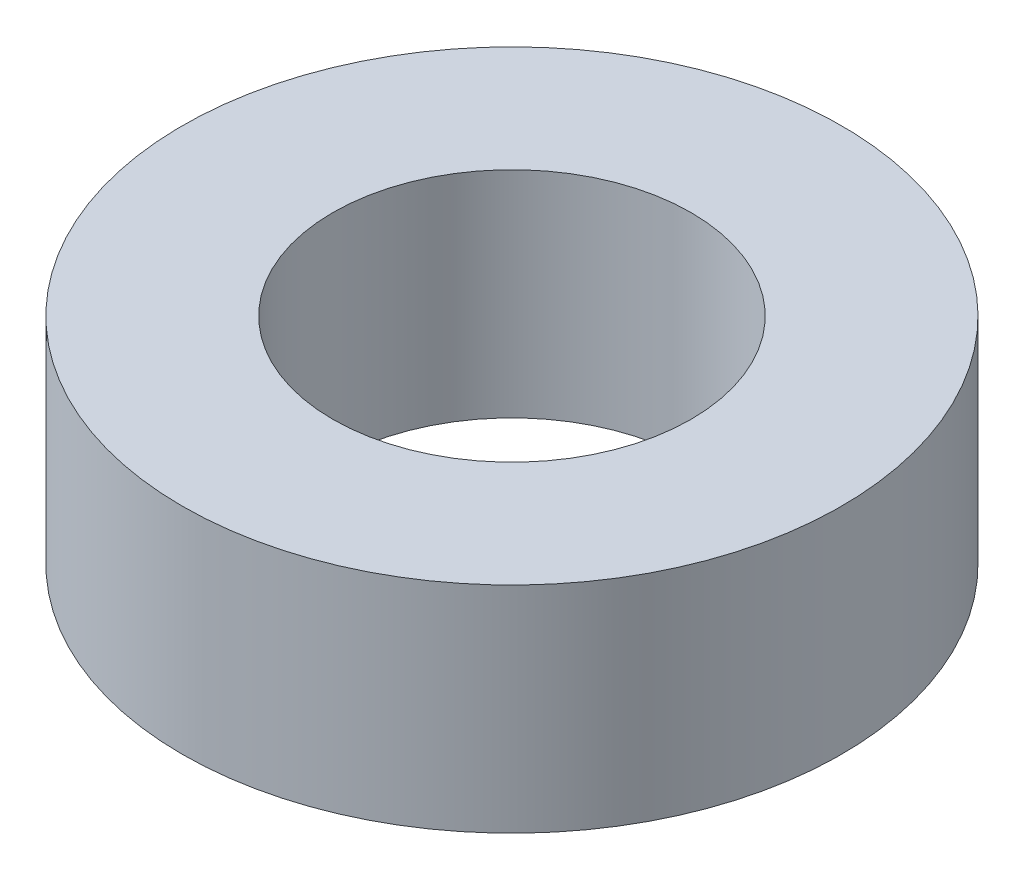
SolidWorks part; units mm, degrees
ref_plane "前视基准面" through (0, 0, 0) normal (0, 0, 1) x (1, 0, 0)
ref_plane "上视基准面" through (0, 0, 0) normal (0, 1, 0) x (1, 0, 0)
ref_plane "右视基准面" through (0, 0, 0) normal (1, 0, 0) x (0, 0, -1)
sketch "草图1" plane through (0, 0, 0) normal (0, 1, 0) x (1, 0, 0)
  circle A0 centre (0, 0) radius 125
  circle A1 centre (0, 0) radius 230
  dimension "D1" = 250
  dimension "D2" = 460
extrude "凸台-拉伸1" add sketch "草图1" along normal blind 150
